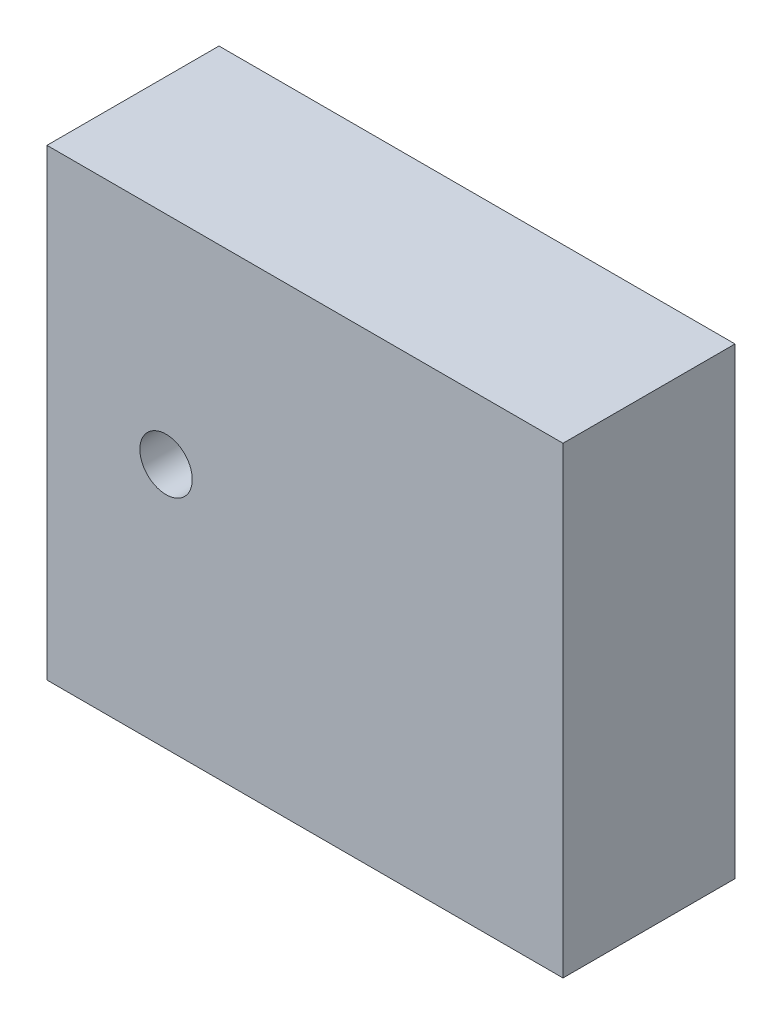
SolidWorks part; units mm, degrees
ref_plane "Ön Düzlem" through (0, 0, 0) normal (0, 0, 1) x (1, 0, 0)
ref_plane "Üst Düzlem" through (0, 0, 0) normal (0, 1, 0) x (1, 0, 0)
ref_plane "Sağ Düzlem" through (0, 0, 0) normal (1, 0, 0) x (0, 0, -1)
sketch "Çizim1" plane through (0, 0, 0) normal (0, 0, 1) x (1, 0, 0)
  line L1 (-19.5, -17.5) -> (19.5, -17.5)
  line L2 (-19.5, -17.5) -> (-19.5, 17.5)
  line L3 (-19.5, 17.5) -> (19.5, 17.5)
  line L4 (19.5, -17.5) -> (19.5, 17.5)
  line L5 (-19.5, -17.5) -> (19.5, 17.5) construction
  line L6 (-19.5, 17.5) -> (19.5, -17.5) construction
  circle A0 centre (-10.5, 1.1145) radius 1.9799
  point P0 (0, 0)
  dimension "D3" = 3.9598
  dimension "D4" = 9
  dimension "D1" = 39
  dimension "D2" = 35
extrude "Yükseklik-Ekstrüzyon1" add sketch "Çizim1" along normal blind 13
